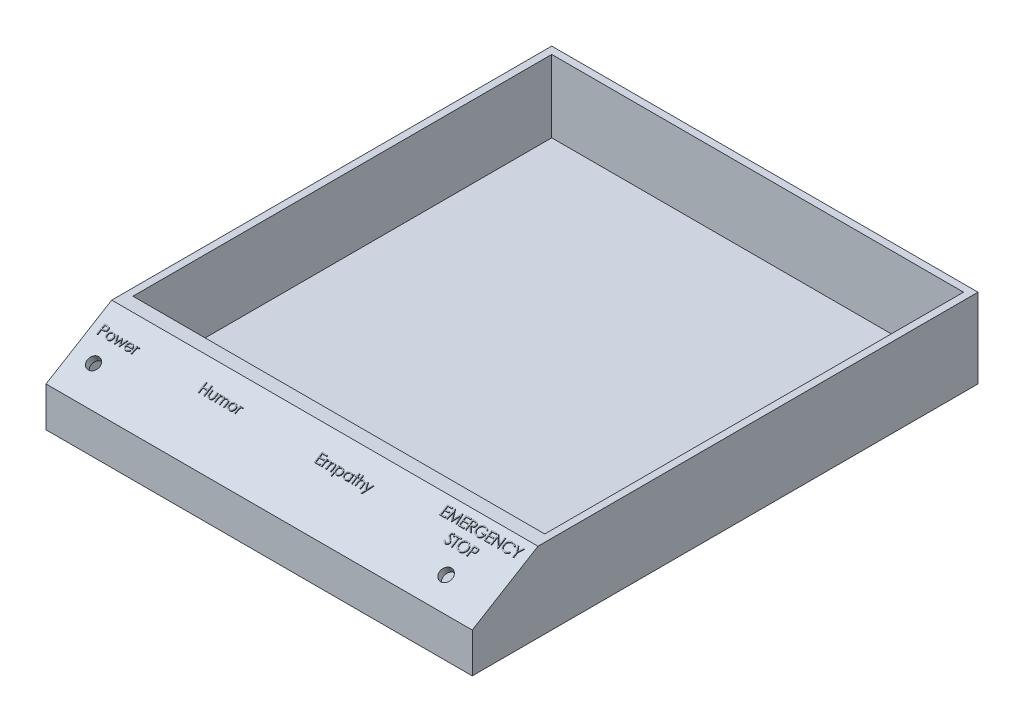
SolidWorks part; units mm, degrees
ref_plane "Front Plane" through (0, 0, 0) normal (0, 0, 1) x (1, 0, 0)
ref_plane "Top Plane" through (0, 0, 0) normal (0, 1, 0) x (1, 0, 0)
ref_plane "Right Plane" through (0, 0, 0) normal (1, 0, 0) x (0, 0, -1)
sketch "Sketch1" plane through (0, 0, 0) normal (1, 0, 0) x (0, 0, -1)
  line L0 (-350, 0) -> (-259.0292, 55)
  line L1 (350, 55) -> (-259.0292, 55)
  line L2 (350, 55) -> (350, -55)
  line L3 (350, -55) -> (-350, -55)
  line L4 (-350, 0) -> (-350, -55)
  line L5 (350, 55) -> (-350, -55) construction
  line L6 (350, -55) -> (-277.7962, 43.6537) construction
  point P0 (0, 0)
  dimension "D1" = 700
extrude "Boss-Extrude1" add sketch "Sketch1" along normal blind 590
shell "Shell1" thickness 10
sketch "Sketch6" plane through (0, 154.963, 93.689) normal (0, 0.8558, 0.5174) x (1, 0, 0)
  line L0 (10, -230.3139) -> (66.593, -230.3139) construction
  line L1 (10, -314.2389) -> (10, 267.6746) construction
  line L3 (150.0739, -230.3139) -> (210.6716, -230.3139) construction
  line L5 (313.2217, -232.7929) -> (403.8485, -232.7929) construction
  line L6 (471.9654, -215.4935) -> (580, -215.4935) construction
  line L7 (580, -314.2389) -> (580, 267.6746) construction
  line L8 (580, -215.4935) -> (471.9654, -215.4935) construction
  text T0 "Power" font "Century Gothic" height in points 48
  text T1 "Humor" font "Century Gothic" height in points 48
  text T2 "Empathy" font "Century Gothic" height in points 48
  text T3 "EMERGENCY\r\n     STOP" font "Century Gothic" height in points 48
extrude "Boss-Extrude3" add sketch "Sketch6" along normal blind 1
sketch "Sketch7" plane through (0, 154.963, 93.689) normal (0, 0.8558, 0.5174) x (1, 0, 0)
  circle A0 centre (29.885, -257.5447) radius 8.5
  dimension "D1" = 17
extrude "Cut-Extrude1" cut sketch "Sketch7" against normal blind 10
sketch "Sketch8" plane through (0, 154.963, 93.689) normal (0, 0.8558, 0.5174) x (1, 0, 0)
  circle A0 centre (523.8722, -264.5746) radius 8.75
  point P2 (523.9683, -264.0689)
  point P3 (523.8722, -264.5746)
  dimension "D1" = 17.5
extrude "Cut-Extrude2" cut sketch "Sketch8" against normal blind 10
